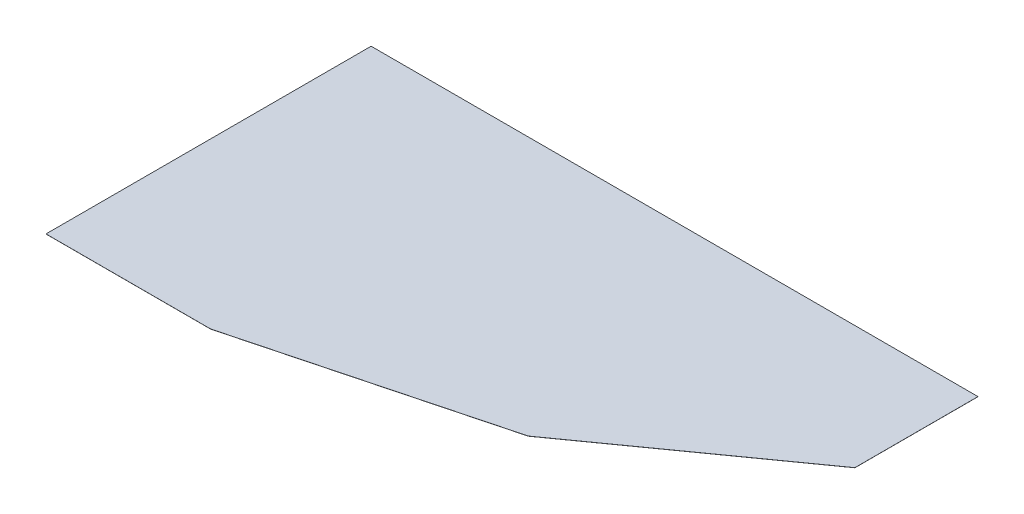
SolidWorks part; units mm, degrees
ref_plane "前视基准面" through (0, 0, 0) normal (0, 0, 1) x (1, 0, 0)
ref_plane "上视基准面" through (0, 0, 0) normal (0, 1, 0) x (1, 0, 0)
ref_plane "右视基准面" through (0, 0, 0) normal (1, 0, 0) x (0, 0, -1)
sketch "草图1" plane through (0, 0, 0) normal (0, 1, 0) x (1, 0, 0)
  line L0 (0, 0) -> (140, 0)
  line L1 (140, 0) -> (140, -28.4)
  line L2 (140, -28.4) -> (96.0282, -59.7445)
  line L3 (96.0282, -59.7445) -> (38, -75)
  line L4 (38, -75) -> (0, -75)
  line L5 (0, -75) -> (0, 0)
  dimension "D1" = 140
  dimension "D2" = 75
  dimension "D3" = 38
  dimension "D4" = 60
  dimension "D5" = 54
  dimension "D6" = 28.4
extrude "凸台-拉伸1" add sketch "草图1" along normal mid plane 0.025
